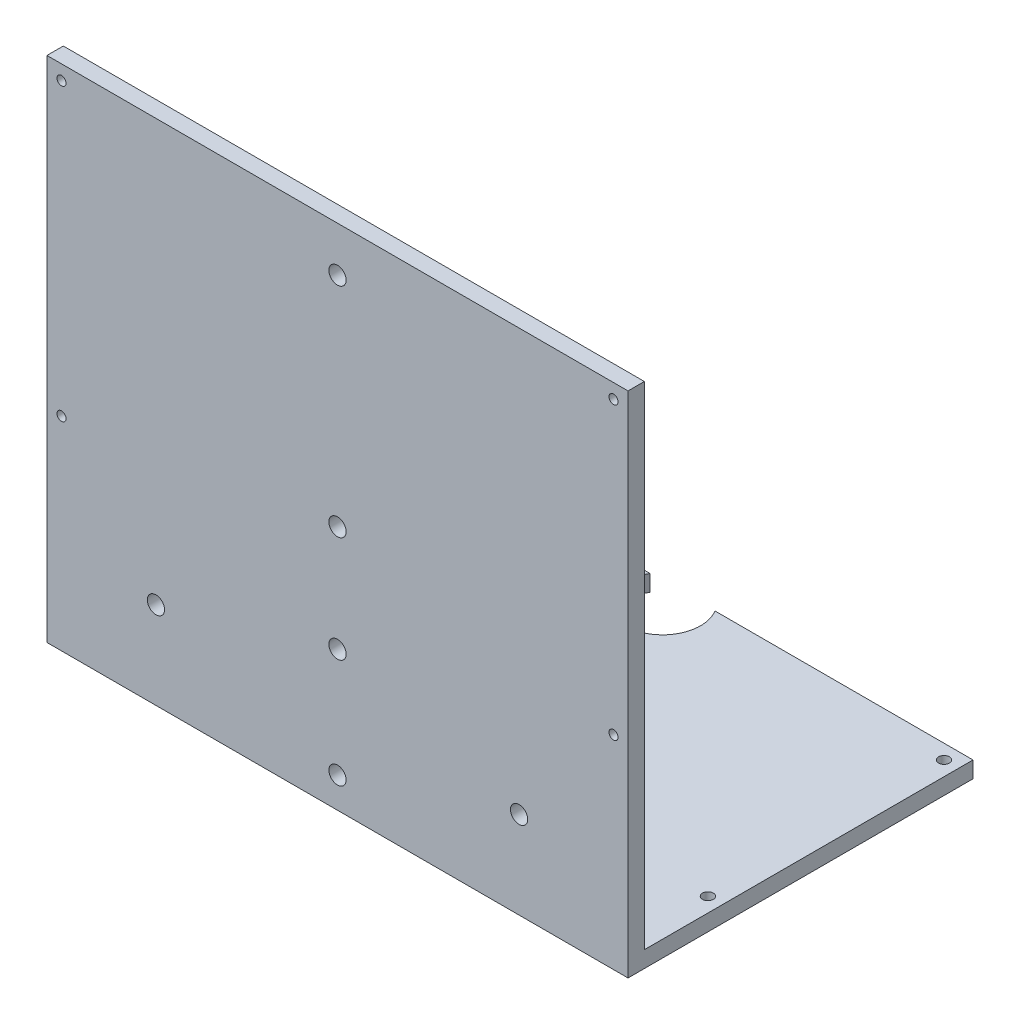
SolidWorks part; units mm, degrees
ref_plane "Front" through (0, 0, 0) normal (0, 0, 1) x (1, 0, 0)
ref_plane "Top" through (0, 0, 0) normal (0, 1, 0) x (1, 0, 0)
ref_plane "Right" through (0, 0, 0) normal (1, 0, 0) x (0, 0, -1)
sketch "Sketch1" plane through (0, 0, 0) normal (0, 1, 0) x (1, 0, 0)
  line L1 (-80, -47.5) -> (80, -47.5)
  line L2 (-80, -47.5) -> (-80, 47.5)
  line L3 (-80, 47.5) -> (80, 47.5)
  line L4 (80, -47.5) -> (80, 47.5)
  line L5 (-80, -47.5) -> (80, 47.5) construction
  line L6 (-80, 47.5) -> (80, -47.5) construction
  point P0 (0, 0)
  dimension "D1" = 95
  dimension "D2" = 160
extrude "Boss-Extrude1" add sketch "Sketch1" along normal blind 4.5
sketch "Sketch2" plane through (0, 4.5, 0) normal (0, 1, 0) x (1, 0, 0)
  line L0 (80, -47.5) -> (80, 47.5) construction
  line L2 (80, 47.5) -> (-80, 47.5) construction
  line L3 (-80, 47.5) -> (-80, -47.5) construction
  circle A0 centre (76, -21.5) radius 1.5
  circle A1 centre (-76, -21.5) radius 1.5
  circle A2 centre (-76, 43.5) radius 1.5
  circle A3 centre (76, 43.5) radius 1.5
  dimension "D1" = 3
  dimension "D2" = 4
  dimension "D3" = 65
  dimension "D6" = 4
  dimension "D7" = 4
  dimension "D4" = 2
  dimension "D5" = 2
extrude "Cut-Extrude1" cut sketch "Sketch2" against normal blind 5
sketch "Sketch5" plane through (0, 4.5, 0) normal (0, 1, 0) x (1, 0, 0)
  line L0 (-80, 47.5) -> (-80, -47.5) construction
  line L1 (80, -47.5) -> (-80, -47.5)
  line L2 (80, -47.5) -> (80, -43)
  line L3 (80, -43) -> (-80, -43)
  line L4 (-80, -47.5) -> (-80, -43)
  dimension "D1" = 4.5
extrude "Boss-Extrude2" add sketch "Sketch5" along normal blind 135.5
sketch "Sketch7" plane through (0, 0, 43) normal (0, 0, -1) x (-1, 0, 0)
  line L0 (-80, 140) -> (80, 140) construction
  line L1 (80, 140) -> (80, 4.5) construction
  line L3 (-80, 140) -> (-80, 4.5) construction
  circle A0 centre (76, 136) radius 1.25
  circle A1 centre (-76, 136) radius 1.25
  circle A2 centre (-76, 56) radius 1.25
  circle A3 centre (76, 56) radius 1.25
  dimension "D1" = 2
  dimension "D3" = 2.5
  dimension "D4" = 4
  dimension "D5" = 4
  dimension "D6" = 80
  dimension "D7" = 4
  dimension "D2" = 2
extrude "Cut-Extrude2" cut sketch "Sketch7" against normal blind 5
sketch "Sketch9" plane through (0, 4.5, 0) normal (0, 1, 0) x (1, 0, 0)
  line L0 (80, -43) -> (80, 47.5) construction
  line L1 (80, 47.5) -> (-80, 47.5) construction
  line L2 (-80, 47.5) -> (-80, -43) construction
  line L4 (80, -43) -> (-80, -43) construction
  circle A0 centre (0, 42) radius 10.5
  circle A2 centre (-45.9177, 40.6059) radius 5
  circle A3 centre (-28.55, 43.75) radius 1.4
  circle A4 centre (-55.25, 30.17) radius 1.4
  dimension "D3" = 21
  dimension "D4" = 2.8
  dimension "D5" = 10
  dimension "D6" = 2.8
  dimension "D9" = 17.65
  dimension "D2" = 85
  dimension "D1" = 80
  dimension "D7" = 17.33
  dimension "D8" = 24.75
  dimension "D10" = 14
  dimension "D11" = 3.75
  dimension "D12" = 51.45
extrude "Cut-Extrude3" cut sketch "Sketch9" against normal blind 5
sketch "Sketch10" plane through (0, 0, 43) normal (0, 0, -1) x (-1, 0, 0)
  line L0 (80, 140) -> (80, 0) construction
  line L3 (-80, 4.5) -> (80, 4.5) construction
  circle A0 centre (0, 8.4) radius 2.375
  circle A1 centre (0, 38.4) radius 2.375
  circle A2 centre (0, 67.6) radius 2.375
  circle A3 centre (0, 127.6) radius 2.375
  circle A4 centre (-50, 24) radius 2.375
  circle A5 centre (50, 24) radius 2.375
  dimension "D1" = 4.75
  dimension "D2" = 4.75
  dimension "D3" = 4.75
  dimension "D4" = 4.75
  dimension "D5" = 4.75
  dimension "D6" = 4.75
  dimension "D9" = 50
  dimension "D11" = 29.2
  dimension "D12" = 60
  dimension "D13" = 30
  dimension "D14" = 3.9
  dimension "D15" = 15.6
  dimension "D7" = 30
  dimension "D8" = 100
  dimension "D10" = 50
extrude "Cut-Extrude4" cut sketch "Sketch10" against normal blind 10
